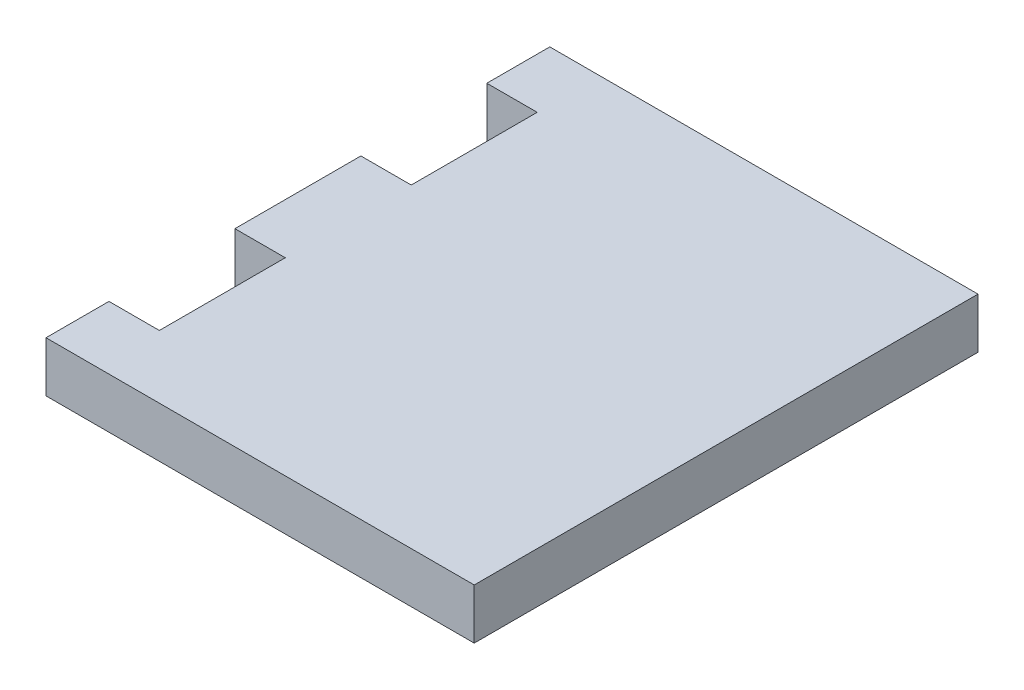
SolidWorks part; units mm, degrees
ref_plane "Front Plane" through (0, 0, 0) normal (0, 0, 1) x (1, 0, 0)
ref_plane "Top Plane" through (0, 0, 0) normal (0, 1, 0) x (1, 0, 0)
ref_plane "Right Plane" through (0, 0, 0) normal (1, 0, 0) x (0, 0, -1)
sketch "Sketch1" plane through (0, 0, 0) normal (0, 1, 0) x (1, 0, 0)
  line L0 (-2, 13.2967) -> (-2, -16.3004) construction
  line L1 (-15, 10) -> (15, 10)
  line L2 (-15, 10) -> (-15, -10)
  line L3 (-15, -10) -> (15, -10)
  line L4 (15, 10) -> (15, -10)
  line L5 (-15, 10) -> (15, -10) construction
  line L6 (-15, -10) -> (15, 10) construction
  line L7 (-2, 7.5) -> (-2, 2.5)
  line L8 (-2, 7.5) -> (0, 7.5)
  line L9 (-2, 2.5) -> (0, 2.5)
  line L10 (0, 7.5) -> (0, 2.5)
  line L11 (-2, -2.5) -> (-2, -7.5)
  line L12 (-2, -2.5) -> (0, -2.5)
  line L13 (-2, -7.5) -> (0, -7.5)
  line L14 (0, -2.5) -> (0, -7.5)
  point P0 (0, 0)
  point P8 (0, 5)
  point P15 (0, -5)
  dimension "D1" = 20
  dimension "D2" = 30
  dimension "D3" = 17
  dimension "D4" = 2
  dimension "D5" = 2
  dimension "D6" = 5
  dimension "D7" = 5
  dimension "D8" = 5
  dimension "D9" = 5
extrude "Boss-Extrude1" add sketch "Sketch1" along normal blind 2
sketch "Sketch2" plane through (0, 2, 0) normal (0, 1, 0) x (1, 0, 0)
  line L0 (-10, 12.4144) -> (-10, -13.471) construction
  line L1 (-15, 10) -> (-15, -10) construction
  line L2 (15, 10) -> (-15, 10) construction
  line L3 (-15, -10) -> (15, -10) construction
  circle A0 centre (-10, 5) radius 1.5
  circle A1 centre (-10, -5) radius 1.5
  dimension "D2" = 3
  dimension "D3" = 3
  dimension "D1" = 5
  dimension "D4" = 5
  dimension "D5" = 5
extrude "Cut-Extrude1" cut sketch "Sketch2" against normal blind 10
sketch "Sketch3" plane through (0, 2, 0) normal (0, 1, 0) x (1, 0, 0)
  line L0 (15, 10) -> (-15, 10) construction
  line L1 (-15, -10) -> (-2, -10)
  line L2 (-15, -10) -> (-15, 10)
  line L3 (-15, 10) -> (-2, 10)
  line L4 (-2, -10) -> (-2, 10)
  line L5 (-2, 7.5) -> (-2, 2.5) construction
extrude "Cut-Extrude2" cut sketch "Sketch3" against normal blind 10
